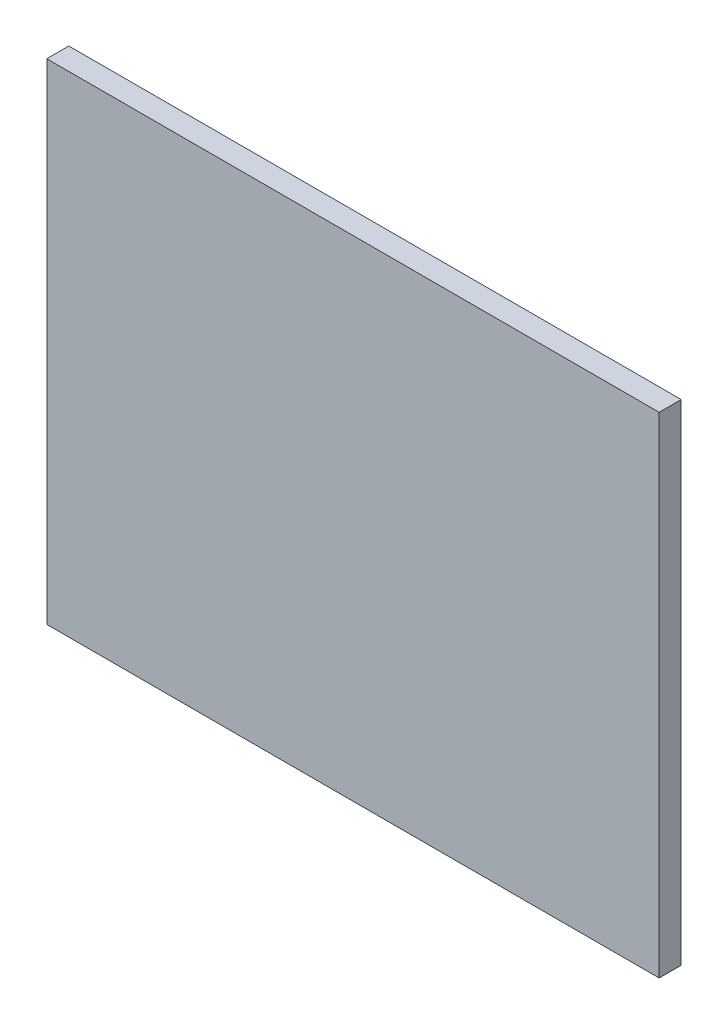
SolidWorks part; units mm, degrees
ref_plane "Piano frontale" through (0, 0, 0) normal (0, 0, 1) x (1, 0, 0)
ref_plane "Piano superiore" through (0, 0, 0) normal (0, 1, 0) x (1, 0, 0)
ref_plane "Piano destro" through (0, 0, 0) normal (1, 0, 0) x (0, 0, -1)
sketch "Schizzo1" plane through (0, 0, 0) normal (0, 0, 1) x (1, 0, 0)
  line L1 (-250, 200) -> (250, 200)
  line L2 (-250, 200) -> (-250, -200)
  line L3 (-250, -200) -> (250, -200)
  line L4 (250, 200) -> (250, -200)
  line L5 (-250, 200) -> (250, -200) construction
  line L6 (-250, -200) -> (250, 200) construction
  point P0 (0, 0)
  dimension "D1" = 400
  dimension "D2" = 500
extrude "Estrusione-Estrusione1" add sketch "Schizzo1" along normal blind 18
equation "\"m\"=500"
